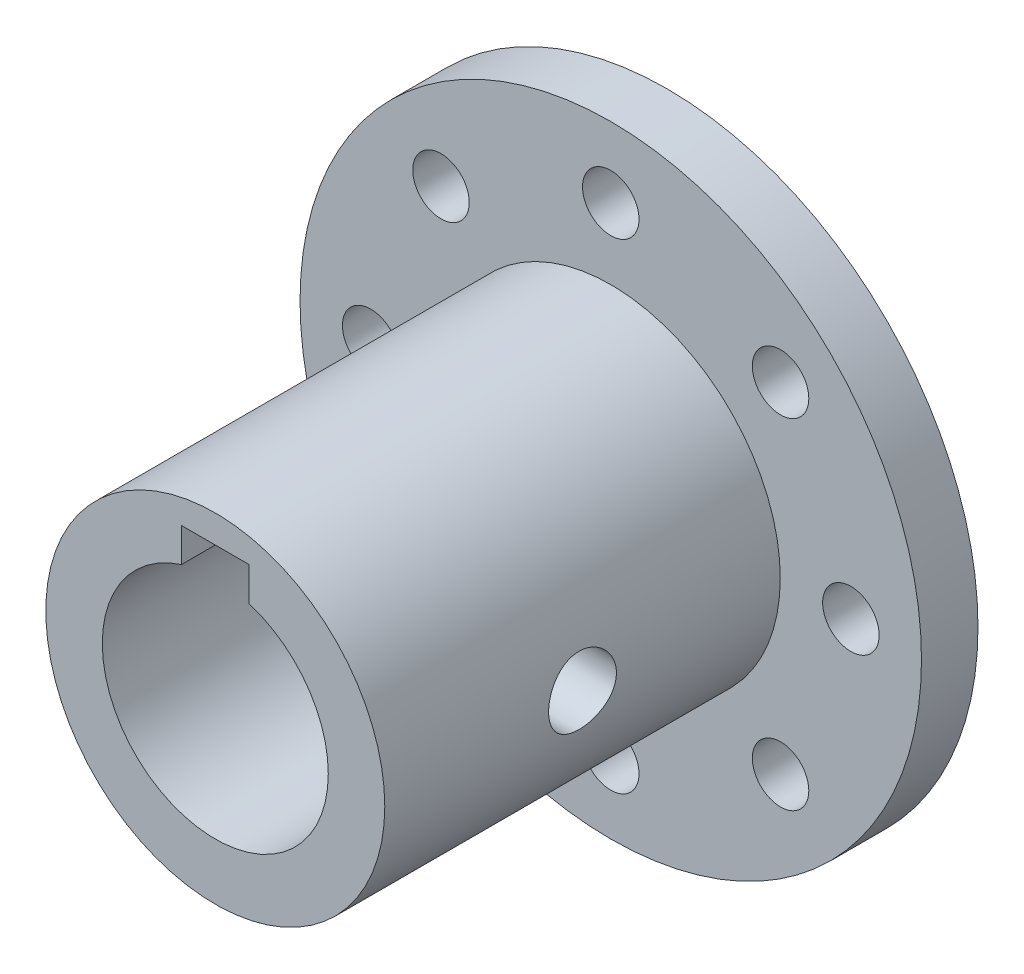
SolidWorks part; units mm, degrees
ref_plane "Alzado" through (0, 0, 0) normal (0, 0, 1) x (1, 0, 0)
ref_plane "Planta" through (0, 0, 0) normal (0, 1, 0) x (1, 0, 0)
ref_plane "Vista lateral" through (0, 0, 0) normal (1, 0, 0) x (0, 0, -1)
sketch "Croquis1" plane through (0, 0, 0) normal (0, 0, 1) x (1, 0, 0)
  circle A0 centre (0, 0) radius 27.5
  dimension "D1" = 55
extrude "Saliente-Extruir1" add sketch "Croquis1" along normal blind 5
sketch "Croquis2" plane through (0, 0, 5) normal (0, 0, 1) x (1, 0, 0)
  circle A0 centre (0, 0) radius 15
  dimension "D1" = 30
extrude "Saliente-Extruir2" add sketch "Croquis2" along normal blind 35
sketch "Croquis3" plane through (0, 0, 40) normal (0, 0, 1) x (1, 0, 0)
  circle A0 centre (0, 0) radius 10
  dimension "D1" = 20
sketch "Croquis5" plane through (0, 0, 5) normal (0, 0, 1) x (1, 0, 0)
  line L0 (0, 21.25) -> (0, -21.25) construction
  line L1 (-21.25, 0) -> (21.25, 0) construction
  line L2 (0, 0) -> (15.026, 15.026) construction
  line L3 (0, 0) -> (-15.026, -15.026) construction
  line L4 (-15.026, 15.026) -> (15.026, -15.026) construction
  circle A0 centre (0, 0) radius 21.25 construction
  circle A2 centre (0, 0) radius 15 construction
  circle A4 centre (0, 21.25) radius 2.5
  circle A5 centre (0, -21.25) radius 2.5
  circle A6 centre (21.25, 0) radius 2.5
  circle A7 centre (-21.25, 0) radius 2.5
  circle A8 centre (15.026, 15.026) radius 2.5
  circle A9 centre (-15.026, 15.026) radius 2.5
  circle A10 centre (-15.026, -15.026) radius 2.5
  circle A11 centre (15.026, -15.026) radius 2.5
  dimension "D1" = 6.25
  dimension "D2" = 45
  dimension "D3" = 5
extrude "Cortar-Extruir4" cut sketch "Croquis5" against normal blind 5
extrude "Cortar-Extruir5" cut sketch "Croquis3" against normal blind 35
sketch "Croquis7" plane through (0, 0, 40) normal (0, 0, 1) x (1, 0, 0)
  line L0 (-3, 12.5394) -> (-3, 9.5394)
  line L1 (0, 12.5394) -> (3, 12.5394)
  line L2 (0, 12.5394) -> (-3, 12.5394)
  line L3 (3, 12.5394) -> (3, 9.5394)
  circle A2 centre (0, 0) radius 10 construction
  circle A3 centre (0, 0) radius 10 construction
  arc A4 (3, 9.5394) -> (-3, 9.5394) centre (0, 0) ccw
  dimension "D1" = 3
  dimension "D2" = 3
  dimension "D3" = 3
  dimension "D4" = 3
extrude "Cortar-Extruir6" cut sketch "Croquis7" against normal blind 32
sketch "Croquis8" plane through (0, 0, 0) normal (0, 0, -1) x (-1, 0, 0)
  circle A0 centre (0, 0) radius 12.5
  circle A1 centre (0, 0) radius 10
  dimension "D1" = 25
  dimension "D2" = 20
extrude "Saliente-Extruir4" add sketch "Croquis8" along normal blind 1
sketch "Croquis9" plane through (0, 0, 0) normal (1, 0, 0) x (0, 0, -1)
  line L0 (-40, 0) -> (1, 0) construction
  line L1 (-40, 15) -> (-40, -15) construction
  line L2 (1, -12.5) -> (1, 12.5) construction
  line L3 (-22.5, 15) -> (-22.5, -15) construction
  line L4 (-5, 15) -> (-40, 15) construction
  line L5 (-40, -15) -> (-5, -15) construction
  circle A1 centre (-22.5, 0) radius 3
  dimension "D1" = 6
extrude "Cortar-Extruir7" cut sketch "Croquis9" against normal mid plane 50
cosmetic thread "Rosca cosmética1" parameters "D2"=7
cosmetic thread "Rosca cosmética2" parameters "D2"=7
